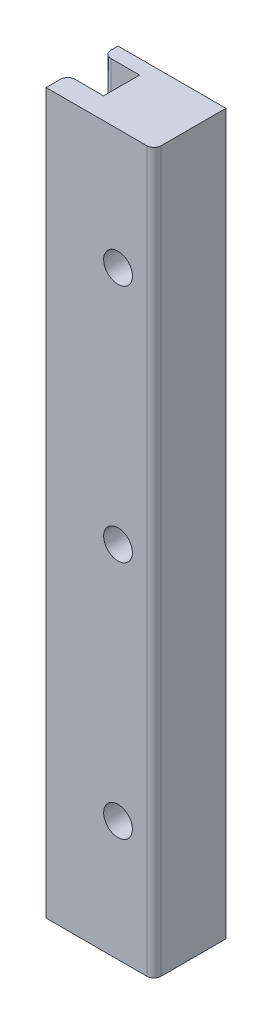
SolidWorks part; units mm, degrees
ref_plane "Front Plane" through (0, 0, 0) normal (0, 0, 1) x (1, 0, 0)
ref_plane "Top Plane" through (0, 0, 0) normal (0, 1, 0) x (1, 0, 0)
ref_plane "Right Plane" through (0, 0, 0) normal (1, 0, 0) x (0, 0, -1)
sketch "Sketch1" plane through (0, 0, 0) normal (0, 1, 0) x (1, 0, 0)
  line L0 (-24.9296, 0) -> (27.7465, 0) construction
  line L1 (0, -18.0986) -> (0, -7) construction
  line L2 (0, 0) -> (15, 0)
  line L3 (15, 0) -> (15, -2)
  line L6 (7, -10) -> (0, -10)
  line L7 (0, -10) -> (0, -7)
  line L8 (0, -7) -> (5, -7)
  line L9 (5, -7) -> (5, -2)
  line L10 (5, -2) -> (0, -2)
  line L11 (0, -2) -> (0, 18.662) construction
  line L12 (0, -2) -> (0, 0)
  line L13 (7, -10) -> (15, -10)
  line L14 (15, -10) -> (15, -2)
  dimension "D1" = 15
  dimension "D2" = 2
  dimension "D3" = 3
  dimension "D4" = 5
  dimension "D6" = 2
  dimension "D7" = 5
extrude "Boss-Extrude1" add sketch "Sketch1" along normal blind 100
fillet "Fillet1" radius 1 3 edges at (0, 50, 7) (0, 50, 2) (15, 50, 10)
sketch "Sketch2" plane through (0, 0, 10) normal (0, 0, 1) x (1, 0, 0)
  line L0 (10, 100) -> (10, 0) construction
  line L1 (0, 100) -> (14, 100) construction
  line L2 (0, 0) -> (14, 0) construction
  line L3 (0, 100) -> (0, 0) construction
  line L4 (0, 50) -> (12, 50) construction
  circle A0 centre (10, 50) radius 2
  circle A1 centre (10, 83.3) radius 2
  circle A2 centre (10, 50) radius 2
  circle A3 centre (10, 16.7) radius 2
  dimension "D2" = 4
  dimension "D1" = 10
  dimension "D3" = 2
  dimension "D4" = 2
extrude "Cut-Extrude1" cut sketch "Sketch2" against normal blind 10 contours A3 | A1 | A0
